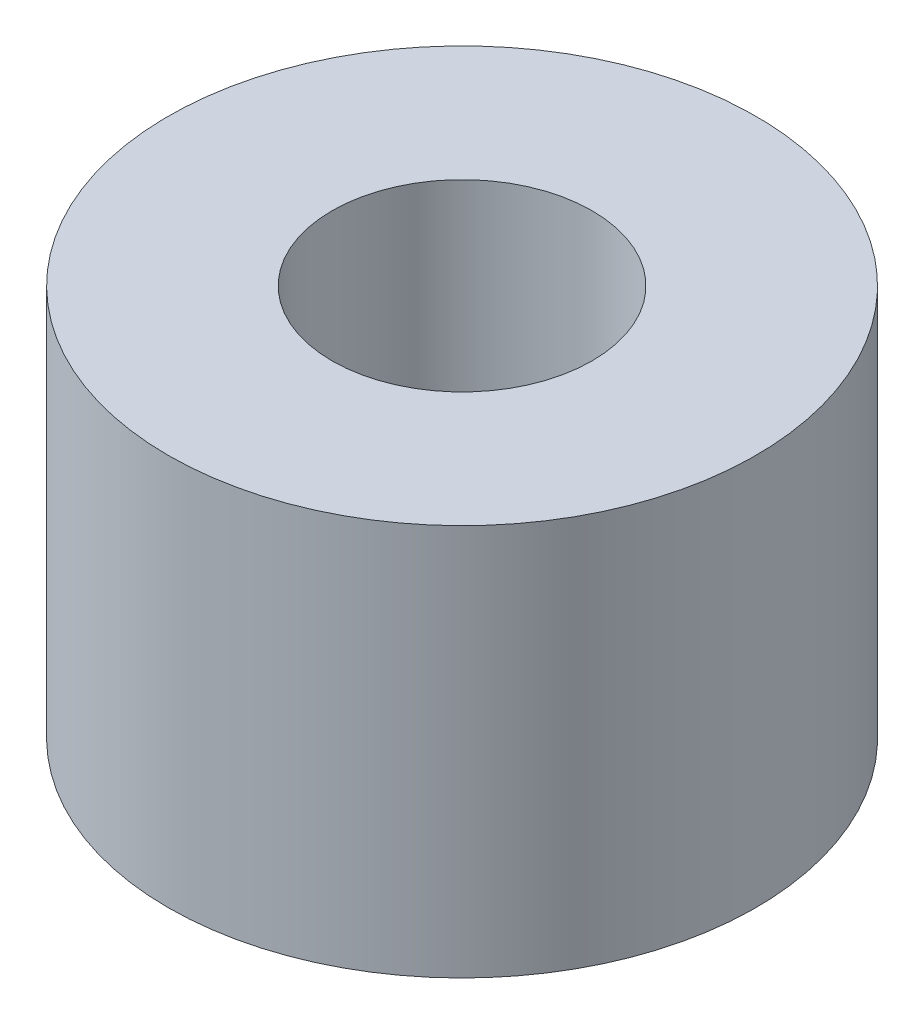
SolidWorks part; units mm, degrees
ref_plane "Front Plane" through (0, 0, 0) normal (0, 0, 1) x (1, 0, 0)
ref_plane "Top Plane" through (0, 0, 0) normal (0, 1, 0) x (1, 0, 0)
ref_plane "Right Plane" through (0, 0, 0) normal (1, 0, 0) x (0, 0, -1)
sketch "Sketch1" plane through (0, 0, 0) normal (0, 1, 0) x (1, 0, 0)
  circle A0 centre (0, 0) radius 2.1082
  circle A1 centre (0, 0) radius 4.7625
  dimension "D1" = 9.525
  dimension "D2" = 4.2164
extrude "Boss-Extrude1" add sketch "Sketch1" along normal blind 6.35
